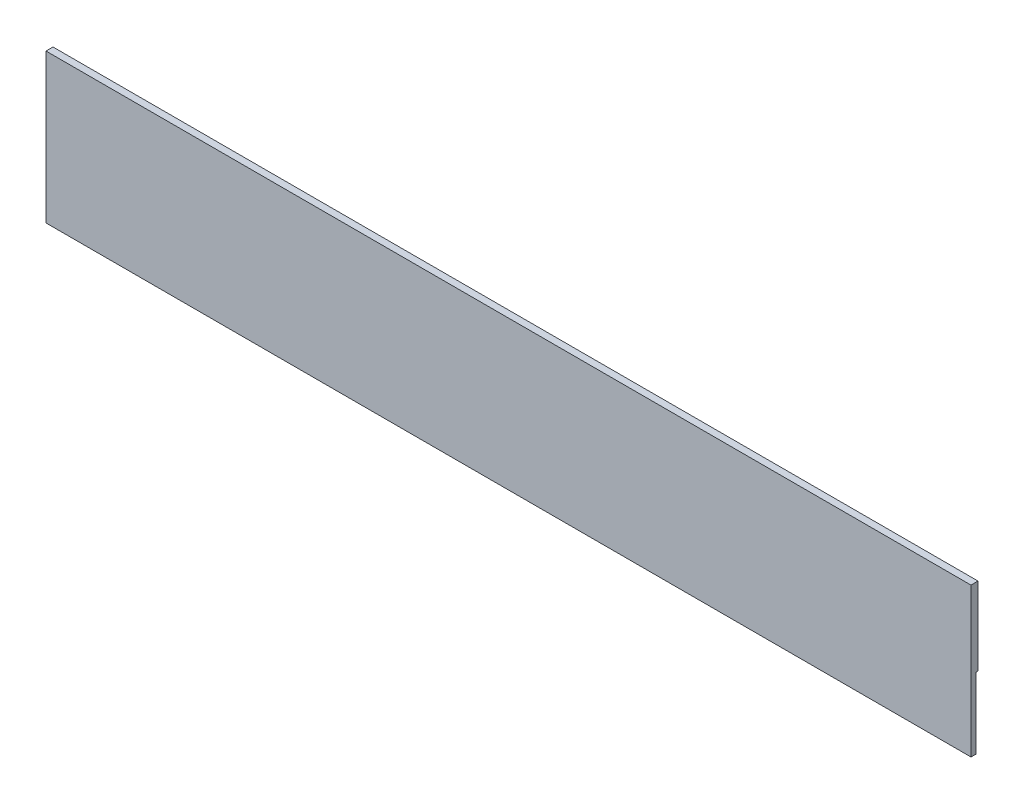
SolidWorks part; units mm, degrees
ref_plane "Front Plane" through (0, 0, 0) normal (0, 0, 1) x (1, 0, 0)
ref_plane "Top Plane" through (0, 0, 0) normal (0, 1, 0) x (1, 0, 0)
ref_plane "Right Plane" through (0, 0, 0) normal (1, 0, 0) x (0, 0, -1)
sketch "Sketch2" plane through (0, 0, 0) normal (0, 0, 1) x (1, 0, 0)
  line L1 (0, 0) -> (13411.2, 0)
  line L2 (0, 0) -> (0, 2159)
  line L3 (0, 2159) -> (13411.2, 2159)
  line L4 (13411.2, 0) -> (13411.2, 2159)
  dimension "D1" = 13411.2
  dimension "D2" = 2159
extrude "Boss-Extrude1" add sketch "Sketch2" along normal blind 76.2
sketch "Sketch4" plane through (0, 0, 0) normal (0, 0, -1) x (-1, 0, 0)
  line L0 (-13411.2, 0) -> (-13411.2, 2159) construction
  line L1 (-13411.2, 1028.7) -> (0, 1028.7)
  line L2 (-13411.2, 1028.7) -> (-13411.2, 2159)
  line L3 (-13411.2, 2159) -> (0, 2159)
  line L4 (0, 1028.7) -> (0, 2159)
  line L5 (-2209.8, 0) -> (-11125.2, 0) construction
  dimension "D1" = 1028.7
extrude "Boss-Extrude2" add sketch "Sketch4" along normal blind 25.4
